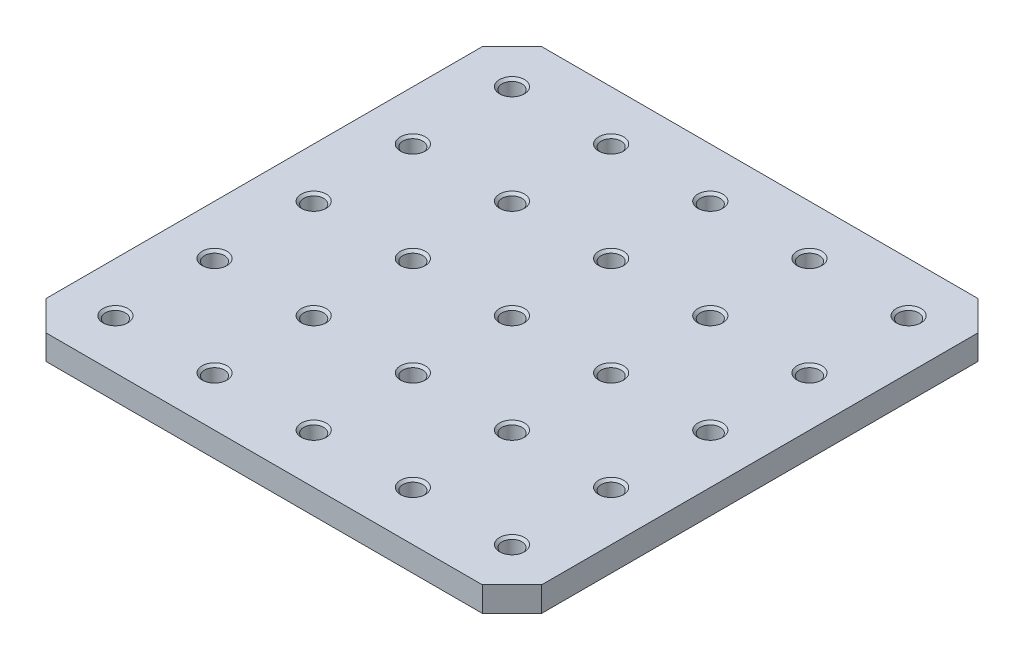
SolidWorks part; units mm, degrees
ref_plane "Front Plane" through (0, 0, 0) normal (0, 0, 1) x (1, 0, 0)
ref_plane "Top Plane" through (0, 0, 0) normal (0, 1, 0) x (1, 0, 0)
ref_plane "Right Plane" through (0, 0, 0) normal (1, 0, 0) x (0, 0, -1)
sketch "Sketch1" plane through (0, 0, 0) normal (0, 1, 0) x (1, 0, 0)
  line L1 (-63.5, 63.5) -> (63.5, 63.5)
  line L2 (-63.5, 63.5) -> (-63.5, -63.5)
  line L3 (-63.5, -63.5) -> (63.5, -63.5)
  line L4 (63.5, 63.5) -> (63.5, -63.5)
  line L5 (-63.5, 63.5) -> (63.5, -63.5) construction
  line L6 (-63.5, -63.5) -> (63.5, 63.5) construction
  point P0 (0, 0)
  dimension "D1" = 127
  dimension "D2" = 127
extrude "Boss-Extrude1" add sketch "Sketch1" along normal blind 6.35
hole_wizard "Tap Drill for 1/4-20 Tap1" [suppressed] positions "3DSketch1" profile "Sketch3" hole size "1/4-20" standard "ANSI Inch"
sketch3d "3DSketch1"
  line L0 (76.2, 12.7, 76.2) -> (76.2, 0, 76.2) construction
  line L1 (-76.2, 12.7, 76.2) -> (76.2, 12.7, 76.2) construction
  point P0 (63.5, 6.35, 76.2)
  dimension "D1" = 12.7
  dimension "D2" = 6.35
sketch "Sketch3" plane through (63.5, 6.35, 76.2) normal (1, 0, 0) x (0, -1, 0)
  line L0 (0, 0) -> (0, 52.3338)
  line L1 (0, 52.3338) -> (2.5527, 50.8)
  line L2 (2.5527, 50.8) -> (2.5527, 0)
  line L5 (2.5527, 0) -> (0, 0)
  line L10 (0, 52.3338) -> (-2.5527, 50.8) construction
  line L11 (0, -6.35) -> (0, 107.95) construction
  dimension "Hole Dia." = 5.1054
  dimension "Hole Depth" = 50.8
  dimension "Drill Angle" = 118
sketch "Sketch4" [suppressed] plane through (0, 0, 76.2) normal (0, 0, 1) x (1, 0, 0)
  point P0 (63.5, 6.35)
sketch "Sketch5" plane through (0, 6.35, 0) normal (0, 1, 0) x (1, 0, 0)
  line L0 (63.5, 63.5) -> (-63.5, 63.5) construction
  line L1 (-63.5, 63.5) -> (-63.5, -63.5) construction
  circle A0 centre (-50.8, 50.8) radius 3.175
  dimension "D1" = 6.35
  dimension "D2" = 12.7
  dimension "D3" = 12.7
hole_wizard "Tap Drill for 1/4-20 Tap2" positions "3DSketch2" profile "Sketch6" hole size "1/4-20" standard "ANSI Inch" end condition through all
sketch3d "3DSketch2"
  point P0 (-50.8, 6.35, -50.8)
sketch "Sketch6" plane through (-50.8, 6.35, -50.8) normal (1, 0, 0) x (0, 0, 1)
  line L0 (0, 0) -> (0, 6.35)
  line L1 (0, 6.35) -> (2.5527, 6.35)
  line L2 (2.5527, 6.35) -> (2.5527, 0.635)
  line L3 (2.5527, 0.635) -> (3.1877, 0)
  line L5 (3.1877, 0) -> (0, 0)
  line L6 (-2.5527, 0.635) -> (-3.1877, 0) construction
  line L11 (0, -6.35) -> (0, 107.95) construction
  dimension "Thru Hole Dia." = 5.1054
  dimension "Thru Hole Depth" = 6.35
  dimension "Near C'Sink Dia." = 6.3754
  dimension "Near C'Sink Angle" = 90
pattern_linear "LPattern1" count 5 spacing 25.4 along (0, 0, 1) count 5 spacing 25.4 along (1, 0, 0) of "Tap Drill for 1/4-20 Tap2"
chamfer "Chamfer1" distance 7.62 angle 45 4 edges at (-63.5, 3.175, -63.5) (-63.5, 3.175, 63.5) (63.5, 3.175, 63.5) (63.5, 3.175, -63.5)
